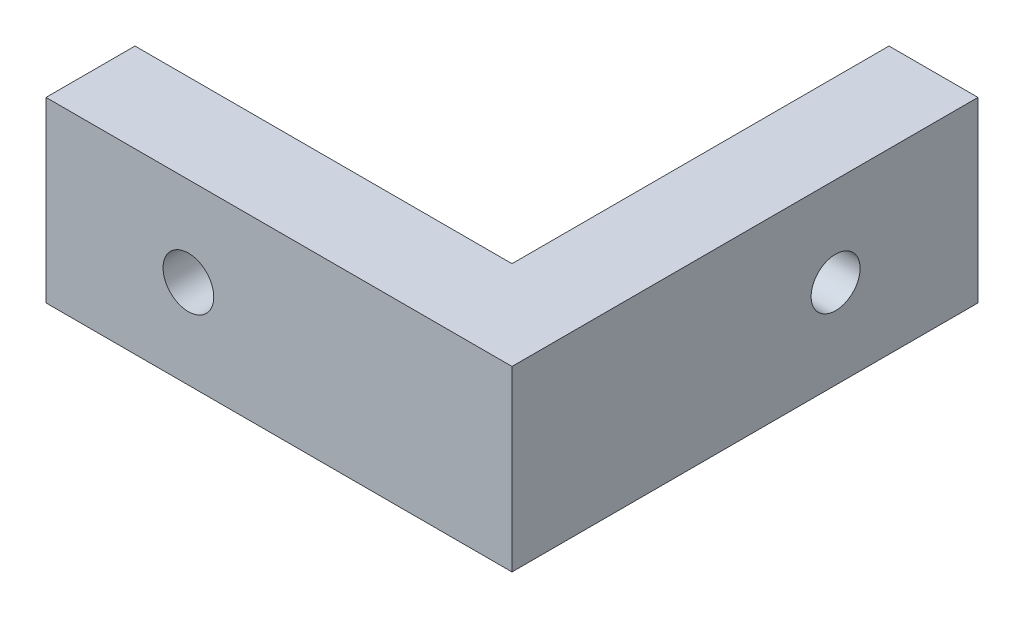
SolidWorks part; units mm, degrees
ref_plane "Front Plane" through (0, 0, 0) normal (0, 0, 1) x (1, 0, 0)
ref_plane "Top Plane" through (0, 0, 0) normal (0, 1, 0) x (1, 0, 0)
ref_plane "Right Plane" through (0, 0, 0) normal (1, 0, 0) x (0, 0, -1)
sketch "Sketch2" plane through (0, 0, 0) normal (0, 1, 0) x (1, 0, 0)
  line L1 (0, 0) -> (-26.18, 0)
  line L3 (-5, 5) -> (-26.18, 5)
  line L4 (-26.18, 0) -> (-26.18, 5)
  line L6 (-5, 5) -> (-5, 26.18)
  line L7 (-5, 26.18) -> (0, 26.18)
  line L8 (0, 0) -> (0, 26.18)
  dimension "D1" = 5
  dimension "D2" = 26.18
  dimension "D3" = 26.18
  dimension "D4" = 5
extrude "Boss-Extrude1" add sketch "Sketch2" along normal blind 10
sketch "Sketch3" plane through (0, 0, 0) normal (0, 0, 1) x (1, 0, 0)
  line L4 (-18.18, 2.5) -> (-18.18, 10.8775) construction
  line L5 (-26.18, 10) -> (-26.18, 0) construction
  line L6 (-26.18, 5) -> (0, 5) construction
  line L7 (0, 10) -> (0, 0) construction
  circle A0 centre (-18.18, 5) radius 1.425
  dimension "D1" = 2.85
  dimension "D2" = 8
extrude "Cut-Extrude2" cut sketch "Sketch3" against normal up to next
sketch "Sketch4" plane through (0, 0, 0) normal (1, 0, 0) x (0, 0, -1)
  line L0 (26.18, 10) -> (26.18, 0) construction
  line L3 (18.18, 5) -> (18.18, 7.5) construction
  line L4 (26.18, 5) -> (0, 5) construction
  line L5 (0, 10) -> (0, 0) construction
  circle A1 centre (18.18, 5) radius 1.375
  dimension "D3" = 8
extrude "Cut-Extrude3" cut sketch "Sketch4" against normal up to next
